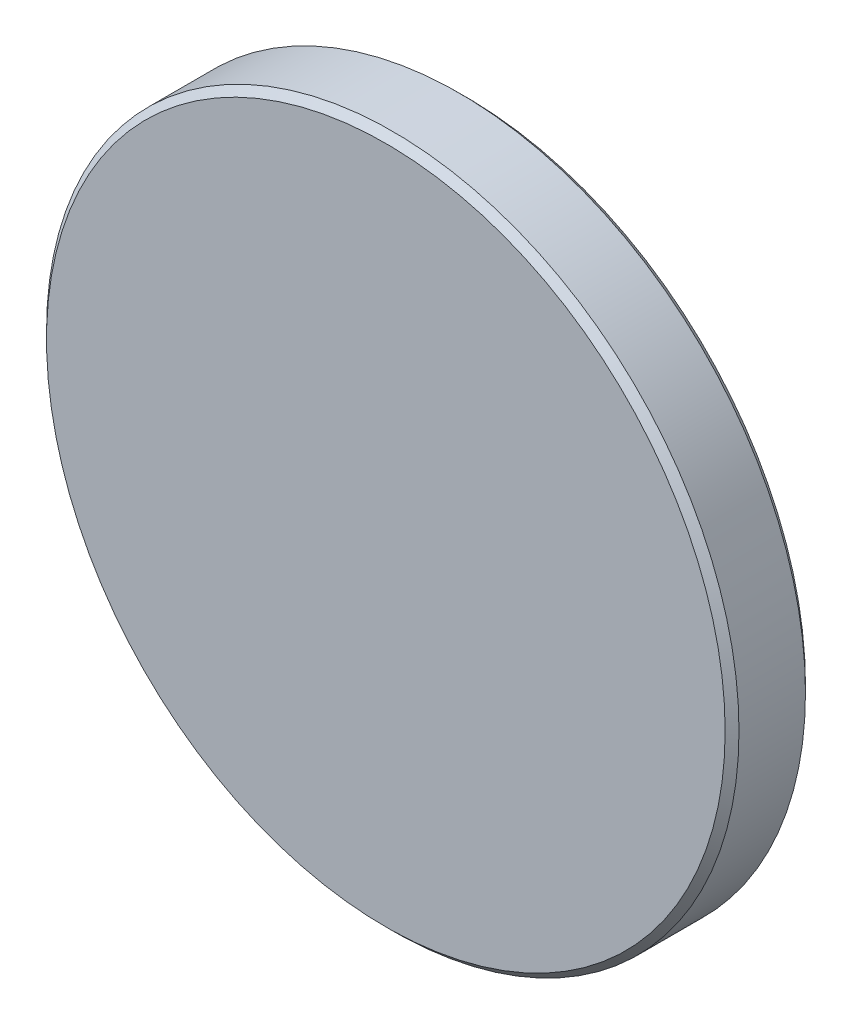
SolidWorks part; units mm, degrees
ref_plane "Plan de face" through (0, 0, 0) normal (0, 0, 1) x (1, 0, 0)
ref_plane "Plan de dessus" through (0, 0, 0) normal (0, 1, 0) x (1, 0, 0)
ref_plane "Plan de droite" through (0, 0, 0) normal (1, 0, 0) x (0, 0, -1)
sketch "Esquisse1" plane through (0, 0, 0) normal (0, 0, 1) x (1, 0, 0)
  circle A1 centre (0, 0) radius 12.5
extrude "Boss.-Extru.2" add sketch "Esquisse1" along normal blind 2.9
chamfer "Chanfrein2" distance 0.25 angle 45 1 edges at (12.5, 0, 2.9)
chamfer "Chanfrein3" distance 0.25 angle 45 1 edges at (12.5, 0, 0)
